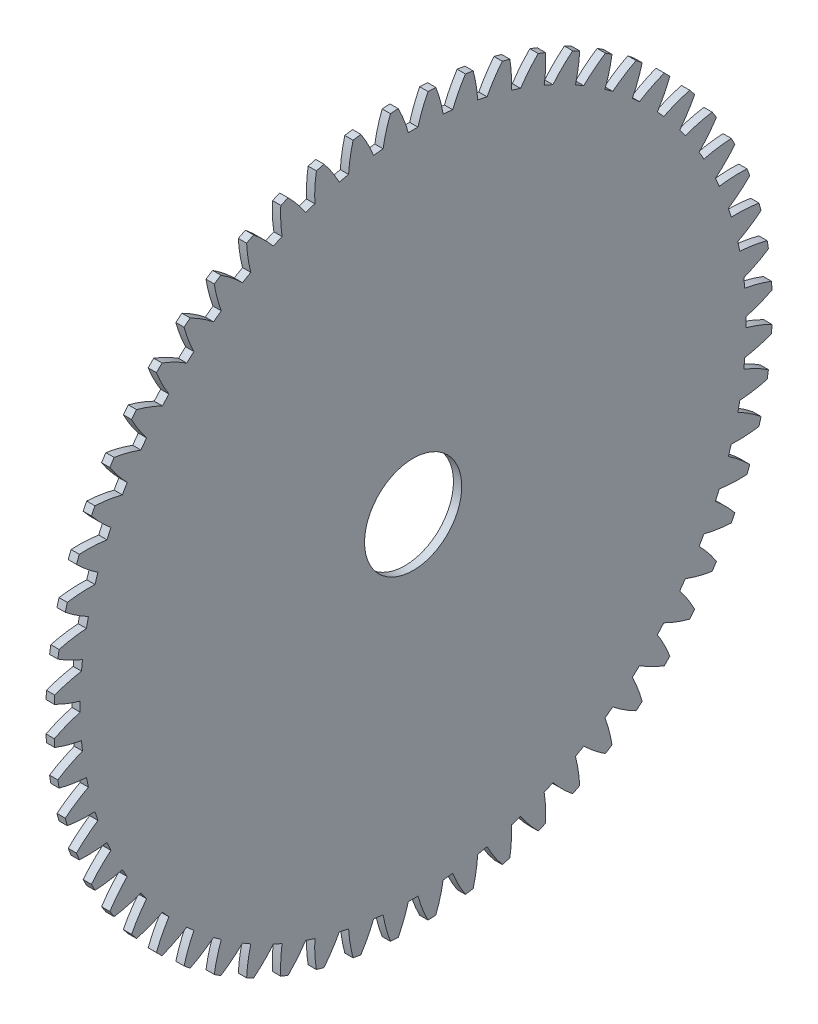
SolidWorks part; units mm, degrees
ref_plane "Plane1" through (0, 0, 0) normal (0, 0, 1) x (1, 0, 0)
ref_plane "Plane2" through (0, 0, 0) normal (0, 1, 0) x (1, 0, 0)
ref_plane "Plane3" through (0, 0, 0) normal (1, 0, 0) x (0, 0, -1)
sketch "HoldingSke" plane through (0, 0, 0) normal (0, 1, 0) x (1, 0, 0)
  line L0 (0, 0) -> (1.7857, -3.0929)
  line L1 (-15, 0) -> (100, 0) construction
  line L2 (0, 0) -> (-2.1039, 2.3779)
  line L3 (0, 0) -> (-11.863, 4.5341)
  line L4 (0, 0) -> (4.318, 7.479)
  line L5 (0, 0) -> (-46.8476, -17.4728)
  line L6 (0, 0) -> (-0.1658, -0.1119)
  line L7 (-2.1039, 2.3779) -> (8.6586, 51.2059)
  line L8 (-76.2, 54.61) -> (-75.9, 54.61)
  line L9 (-71.009, 38.7566) -> (-53.1078, 45.2721)
  line L10 (-76.2, 71.12) -> (104.1128, 71.12)
  line L11 (0, 0) -> (-0.2, 0)
  line L12 (-76.2, 101.6) -> (-76.192, 101.6)
  line L13 (24.9733, 27.94) -> (52.9518, 28.4284)
  line L14 (24.9733, 27.94) -> (24.9743, 27.94)
  line L15 (24.9733, 27.94) -> (100.4006, 29.5858)
  line L16 (-63.627, -0.28) -> (-12.827, -0.28)
  circle A0 centre (0, 0) radius 1
  circle A1 centre (0, 0) radius 8.049
  circle A2 centre (0, 0) radius 37.5
  circle A3 centre (0, 0) radius 1
  dimension "MHD" = 16.098
  dimension "Hub_dia" = 75
  dimension "Bore" = 2
  dimension "MBD" = 2
  dimension "Num_teeth" = 60
  dimension "Pitch_radius" = 180.3128
  dimension "Pitch" = 3.5714
  dimension "Width" = 0.2
  dimension "Overall_len" = 50
  dimension "Show_teeth" = 60
  dimension "Thickness" = 0.2
  dimension "OAL" = 50.0001
  dimension "T_dim" = 0.3
  dimension "Ap" = 20
  dimension "H" = 19.05
  dimension "Backlash" = 0.008
  dimension "Addendum_fac" = 1
  dimension "Dedendum_fac" = 1.25
  dimension "Clearance_fac" = 0.25
  dimension "Dedendum_add" = 0.001
  dimension "Module" = 0.28
sketch "BasProSke" plane through (0, 0, 0) normal (0, 1, 0) x (1, 0, 0)
  line L0 (-10, 0) -> (60, 0) construction
  line L1 (0, 0) -> (0, 8.68)
  line L2 (0, 0) -> (0.2, 0)
  line L3 (0.2, 0) -> (0.2, 8.68)
  line L4 (0.2, 8.68) -> (0, 8.68)
  dimension "Diameter" = 17.36
  dimension "Thickness" = 0.2
revolve "Base-Revolve" add sketch "BasProSke" angle 360 about L0
sketch "TooCutSke" plane through (0, 0, 0) normal (1, 0, 0) x (0, 0, -1)
  line L1 (0, 0) -> (0, 107) construction
  line L2 (0, 0) -> (-0.2339, 8.3967) construction
  line L3 (0, 0) -> (-0.879, 16.7719) construction
  line L4 (-0.2339, 8.3967) -> (-0.4395, 8.386) construction
  arc A0 (0.1158, 8.0482) -> (-0.1158, 8.0482) centre (0, 0) ccw
  arc A1 (0.372, 8.6974) -> (-0.372, 8.6974) centre (0, 0) ccw
  circle A2 centre (0, 0) radius 8.4 construction
  circle A3 centre (0, 0) radius 7.8934 construction
  arc A4 (-0.1158, 8.0482) -> (-0.372, 8.6974) centre (-3.3525, 7.1461) ccw
  arc A5 (0.372, 8.6974) -> (0.1158, 8.0482) centre (3.3525, 7.1461) ccw
  dimension "Root_dia" = 16.098
  dimension "Overcut_dia" = 17.4108
  dimension "Pitch_dia" = 16.8
  dimension "Base_dia" = 15.7868
  dimension "Flank_rad" = 3.36
  dimension "Half_ang" = 3
  dimension "Half_CT" = 0.2059
extrude "ToothCut" cut sketch "TooCutSke" along normal through all
fillet "Breaks" [suppressed] radius 0.0056
fillet "RootFillets" [suppressed] radius 0.071
pattern_circular "TeethCuts" count 60 every 6 about axis through (-10, 0, 0) along (1, 0, 0) of "ToothCut", "RootFillets", "Breaks"
sketch "HubNeaOneSke" plane through (0, 0, 0) normal (-1, 0, 0) x (0, 0, 1)
  circle A0 centre (0, 0) radius 8.049
  dimension "Diameter" = 16.098
extrude "HubNearOne" [suppressed] add sketch "HubNeaOneSke" along normal blind 49.8001
sketch "HubNeaBotSke" plane through (0, 0, 0) normal (-1, 0, 0) x (0, 0, 1)
  circle A0 centre (0, 0) radius 8.049
  dimension "Diameter" = 16.098
extrude "HubNearBoth" [suppressed] add sketch "HubNeaBotSke" along normal blind 24.9
ref_plane "FarPln" through (0.2, 0, 0) normal (1, 0, 0) x (0, 0, -1)
sketch "HubFarSke" plane through (0.2, 0, 0) normal (1, 0, 0) x (0, 0, -1)
  circle A0 centre (0, 0) radius 8.049
  dimension "Diameter" = 16.098
extrude "HubFar" [suppressed] add sketch "HubFarSke" along normal blind 24.9
sketch "BorSke" plane through (0, 0, 0) normal (1, 0, 0) x (0, 0, -1)
  circle A0 centre (0, 0) radius 1.175
  dimension "Diameter" = 2.35
extrude "Bore" cut sketch "BorSke" along normal mid plane 100.0001
sketch "KeySke" plane through (0, 0, 0) normal (1, 0, 0) x (0, 0, -1)
  line L0 (-0.4, 0) -> (-0.4, 1.3)
  line L1 (-0.4, 1.3) -> (0.4, 1.3)
  line L2 (0.4, 1.3) -> (0.4, 0)
  line L3 (0, 0) -> (0, 34) construction
  line L4 (-0.4, 0) -> (0.4, 0)
  dimension "Offset" = 1.3
  dimension "Width" = 0.8
extrude "Keyway" [suppressed] cut sketch "KeySke" along normal mid plane 100.0001
pattern_circular "Keyway2" [suppressed] count 2 every 90 about axis through (-10, 0, 0) along (1, 0, 0)
equation "' \"Module@HoldingSke\" = 6.35"
equation "' \"Num_teeth@HoldingSke\" = 12"
equation "' \"Ap@HoldingSke\" =  20"
equation "' \"Width@HoldingSke\" = 0.5 * 25.4"
equation "' \"Hub_dia@HoldingSke\"= 1 * 25.4"
equation "' \"Overall_len@HoldingSke\" = 1.0 * 25.4"
equation "' \"Bore@HoldingSke\" = 0.75 * 25.4"
equation "' \"T_dim@HoldingSke\" = 0.1 * 25.4"
equation "' \"Width@KeySke\" = 0.25 * 25.4"
equation "' \"Show_teeth@HoldingSke\" = 13"
equation "' \"Backlash@HoldingSke\" = 0.009 * 25.4"
equation "' \"Addendum_fac@HoldingSke\" = 1.0"
equation "' \"Dedendum_fac@HoldingSke\" = 1.25"
equation "' \"Dedendum_add@HoldingSke\" = 0.00005 * 25.4"
equation "' \"Clearance_fac@HoldingSke\" = 0.25"
equation "\"Pitch@HoldingSke\" = 1 / \"Module@HoldingSke\""
equation "\"Overcut_dia@TooCutSke\" = (\"Num_teeth@HoldingSke\" + 2 * \"Addendum_fac@HoldingSke\") / \"Pitch@HoldingSke\" + 0.002 * 25.4"
equation "\"Pitch_dia@TooCutSke\" = \"Num_teeth@HoldingSke\" / \"Pitch@HoldingSke\""
equation "\"Base_dia@TooCutSke\" = \"Num_teeth@HoldingSke\" / \"Pitch@HoldingSke\" * cos((\"Ap@HoldingSke\"  * 3.14159265 / 180))"
equation "\"Root_dia@TooCutSke\" = (\"Num_teeth@HoldingSke\" + 2) / \"Pitch@HoldingSke\" - 2 * (\"Addendum_fac@HoldingSke\" + \"Dedendum_fac@HoldingSke\") / \"Pitch@HoldingSke\" - \"Dedendum_add@HoldingSke\" * 2"
equation "\"Half_ang@TooCutSke\" = 180 / \"Num_teeth@HoldingSke\""
equation "\"Half_CT@TooCutSke\" = \"Num_teeth@HoldingSke\" / \"Pitch@HoldingSke\" * sin((3.14159265 / 2 / \"Num_teeth@HoldingSke\")) / 2 - 7 * \"Backlash@HoldingSke\" / 4"
equation "\"Flank_rad@TooCutSke\" = \"Num_teeth@HoldingSke\" / \"Pitch@HoldingSke\" / 5"
equation "\"Radius@RootFillets\" = \"Clearance_fac@HoldingSke\" / \"Pitch@HoldingSke\" + \"Dedendum_add@HoldingSke\""
equation "\"Break_rad@Breaks\" = 0.02 / \"Pitch@HoldingSke\""
equation "\"Thickness@HoldingSke\" = \"Width@HoldingSke\""
equation "\"OAL@HoldingSke\" = \"Thickness@HoldingSke\""
equation "\"MHD@HoldingSke\" = (\"Num_teeth@HoldingSke\" + 2) / \"Pitch@HoldingSke\" - 2 * (\"Addendum_fac@HoldingSke\" + \"Dedendum_fac@HoldingSke\")  / \"Pitch@HoldingSke\" - \"Dedendum_add@HoldingSke\" * 2"
equation "\"MBD@HoldingSke\" = (\"Num_teeth@HoldingSke\" + 2) / \"Pitch@HoldingSke\" - 2 * (\"Addendum_fac@HoldingSke\" + \"Dedendum_fac@HoldingSke\")  / \"Pitch@HoldingSke\" - \"Dedendum_add@HoldingSke\" * 2 - 0.002 * 25.4"
equation "\"MHD@HoldingSke\" = ((sgn( \"MHD@HoldingSke\" - \"Hub_dia@HoldingSke\" )-1)*( \"MHD@HoldingSke\" - \"Hub_dia@HoldingSke\" ))/-2+ \"Hub_dia@HoldingSke\""
equation "\"MBD@HoldingSke\" = ((sgn( \"MBD@HoldingSke\" - \"Bore@HoldingSke\" )-1)*( \"MBD@HoldingSke\" - \"Bore@HoldingSke\" ))/-2+ \"Bore@HoldingSke\""
equation "\"OAL@HoldingSke\" = ((sgn( \"OAL@HoldingSke\" - \"Overall_len@HoldingSke\" )+1)*( \"OAL@HoldingSke\" - \"Overall_len@HoldingSke\" ))/2 + \"Overall_len@HoldingSke\" + 0.000002 * 25.4"
equation "\"Num_teeth@TeethCuts\" = int( \"Show_teeth@HoldingSke\" ) + 1"
equation "\"Num_teeth@TeethCuts\" = ((sgn( \"Num_teeth@TeethCuts\" - \"Num_teeth@HoldingSke\" )-1)*( \"Num_teeth@TeethCuts\" - \"Num_teeth@HoldingSke\" ))/-2+ \"Num_teeth@HoldingSke\""
equation "\"Num_teeth@TeethCuts\" = ((sgn( \"Num_teeth@TeethCuts\" - 2.0)+1)*( \"Num_teeth@TeethCuts\" - 2.0))/2 +2.0"
equation "\"Angle@TeethCuts\" = 360.0 / \"Num_teeth@HoldingSke\""
equation "\"Diameter@BasProSke\" = (\"Num_teeth@HoldingSke\" + 2 * \"Addendum_fac@HoldingSke\") / \"Pitch@HoldingSke\""
equation "\"Thickness@BasProSke\"  = \"Thickness@HoldingSke\""
equation "' \"Fillet_rad@BasProSke\" =  \"Thickness@HoldingSke\" * 0.05"
equation "\"MHD@HoldingSke\" = ((sgn( \"MHD@HoldingSke\" - \"Root_dia@TooCutSke\" )-1)*( \"MHD@HoldingSke\" - \"Root_dia@TooCutSke\" ))/-2+ \"Root_dia@TooCutSke\""
equation "\"Diameter@HubNeaOneSke\" = \"MHD@HoldingSke\""
equation "\"Length@HubNearOne\" = \"OAL@HoldingSke\" - \"Thickness@BasProSke\""
equation "\"Diameter@HubNeaBotSke\" = \"MHD@HoldingSke\""
equation "\"Length@HubNearBoth\" = ( \"OAL@HoldingSke\" - \"Thickness@BasProSke\" ) / 2.0"
equation "\"Thickness@FarPln\" = \"Thickness@BasProSke\""
equation "\"Diameter@HubFarSke\" = \"MHD@HoldingSke\""
equation "\"Length@HubFar\" = ( \"OAL@HoldingSke\" - \"Thickness@BasProSke\" ) / 2.0"
equation "\"D1@Bore\" = \"OAL@HoldingSke\" * 2.0"
equation "\"D1@Keyway\" = \"OAL@HoldingSke\" * 2.0"
equation "\"Offset@KeySke\" = \"T_dim@HoldingSke\" + \"MBD@HoldingSke\" / 2.0"
